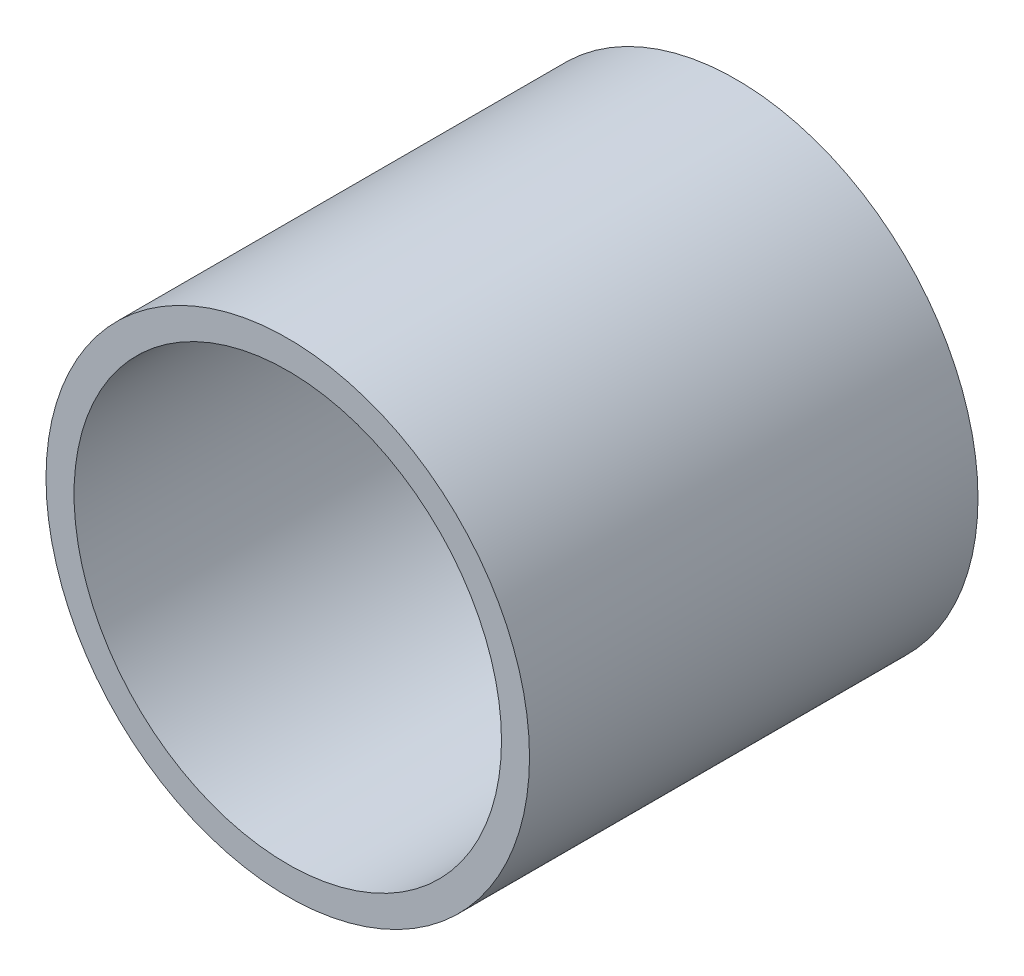
SolidWorks part; units mm, degrees
ref_plane "Front Plane" through (0, 0, 0) normal (0, 0, 1) x (1, 0, 0)
ref_plane "Top Plane" through (0, 0, 0) normal (0, 1, 0) x (1, 0, 0)
ref_plane "Right Plane" through (0, 0, 0) normal (1, 0, 0) x (0, 0, -1)
sketch "Sketch1" plane through (0, 0, 0) normal (0, 0, 1) x (1, 0, 0)
  circle A0 centre (0, 0) radius 109.5375
  dimension "Pipe OD" = 219.075
extrude "Extrude-Thin1" add sketch "Sketch1" along normal mid plane 203.2 thin thin type one direction reverse wall 12.7
